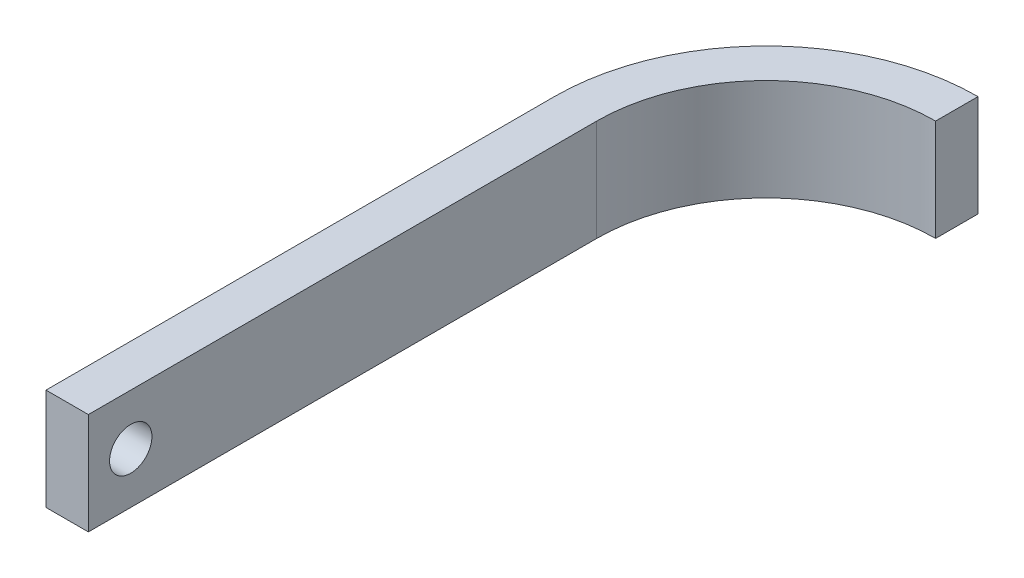
SolidWorks part; units mm, degrees
ref_plane "Front Plane" through (0, 0, 0) normal (0, 0, 1) x (1, 0, 0)
ref_plane "Top Plane" through (0, 0, 0) normal (0, 1, 0) x (1, 0, 0)
ref_plane "Right Plane" through (0, 0, 0) normal (1, 0, 0) x (0, 0, -1)
sketch "Sketch1" plane through (0, 0, 0) normal (0, 1, 0) x (1, 0, 0)
  line L0 (31.75, 101.6) -> (31.75, 107.95)
  line L1 (0, 0) -> (6.35, 0)
  line L2 (0, 0) -> (0, 76.2)
  line L4 (6.35, 0) -> (6.35, 76.2)
  arc A0 (31.75, 107.95) -> (0, 76.2) centre (31.75, 76.2) ccw
  arc A1 (31.75, 101.6) -> (6.35, 76.2) centre (31.75, 76.2) ccw
  dimension "D3" = 63.5
  dimension "D4" = 50.8
  dimension "D1" = 76.2
  dimension "D2" = 6.35
extrude "Boss-Extrude1" add sketch "Sketch1" along normal blind 15.24
sketch "Sketch2" plane through (6.35, 0, 0) normal (1, 0, 0) x (0, 0, -1)
  line L0 (0, 0) -> (76.2, 0) construction
  line L1 (0, 15.24) -> (0, 0) construction
  circle A0 centre (6.35, 7.62) radius 3.175
  dimension "D1" = 6.35
  dimension "D2" = 7.62
  dimension "D3" = 6.35
extrude "Cut-Extrude1" cut sketch "Sketch2" against normal blind 15.24
